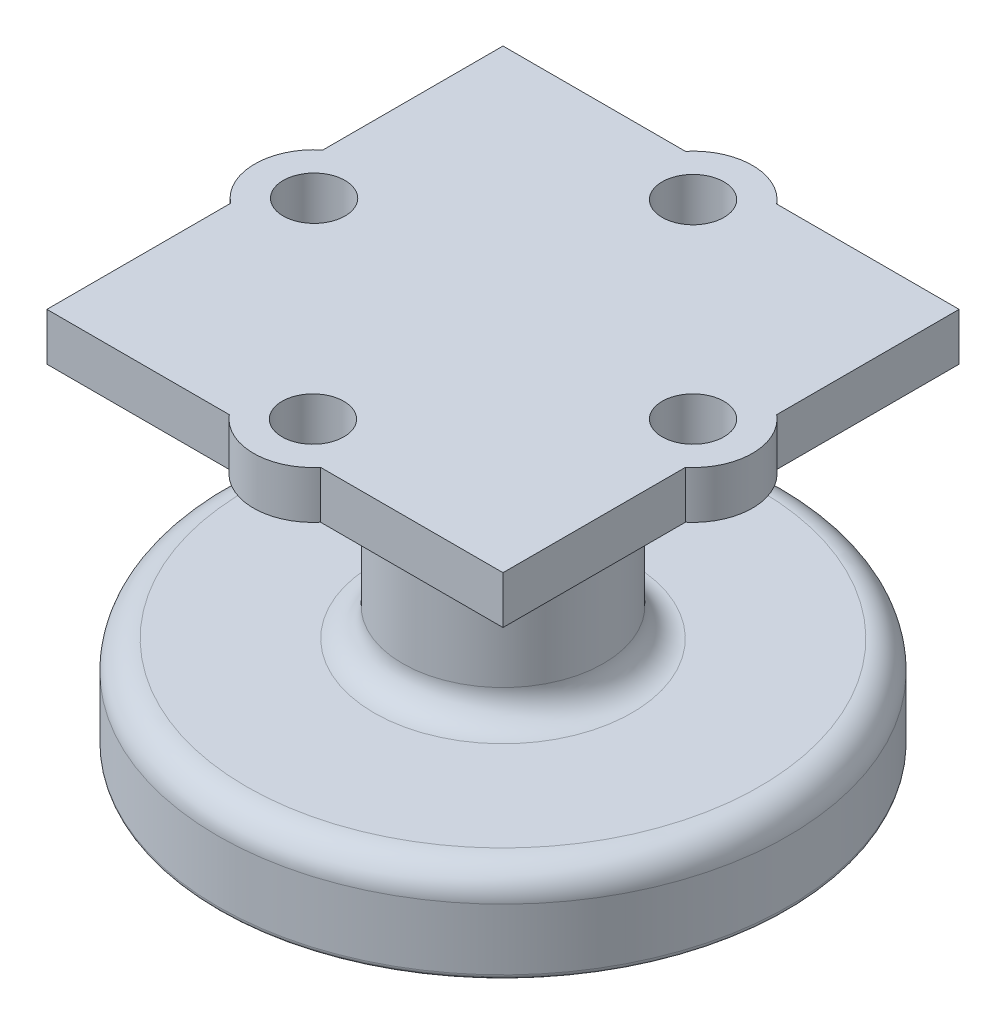
SolidWorks part; units mm, degrees
ref_plane "Спереди" through (0, 0, 0) normal (0, 0, 1) x (1, 0, 0)
ref_plane "Сверху" through (0, 0, 0) normal (0, 1, 0) x (1, 0, 0)
ref_plane "Справа" through (0, 0, 0) normal (1, 0, 0) x (0, 0, -1)
sketch "Sketch1" plane through (0, 0, 0) normal (0, 1, 0) x (1, 0, 0)
  line L0 (-24, -4.6689) -> (-24, -24)
  line L1 (-24, 24) -> (-4.8023, 24)
  line L2 (-24, 24) -> (-24, 5.0436)
  line L3 (-24, -24) -> (-4.8023, -24)
  line L4 (24, 24) -> (24, 4.8023)
  line L5 (-24, 24) -> (24, -24) construction
  line L6 (-24, -24) -> (24, 24) construction
  line L7 (-16, 16) -> (-4.8023, 16)
  line L8 (-16, 16) -> (-16, 4.9342)
  line L9 (-16, -16) -> (-4.8023, -16)
  line L10 (16, 16) -> (16, 4.8023)
  line L11 (-16, 16) -> (16, -16) construction
  line L12 (-16, -16) -> (16, 16) construction
  line L13 (-16, -4.5595) -> (-16, -16)
  line L14 (4.8023, 16) -> (16, 16)
  line L15 (4.8023, 24) -> (24, 24)
  line L16 (16, -4.8023) -> (16, -16)
  line L17 (4.8023, -16) -> (16, -16)
  line L18 (4.8023, -24) -> (24, -24)
  line L19 (24, -4.8023) -> (24, -24)
  circle A0 centre (-20.0657, 0.1873) radius 3.25
  circle A1 centre (0, 20) radius 3.25
  circle A2 centre (20, 0) radius 3.25
  circle A3 centre (0, -20) radius 3.25
  arc A4 (12, -16) -> (6.1732, -19.0234) centre (0, 0) ccw construction
  arc A5 (-24, 5.0436) -> (-24, -4.6689) centre (-20.0657, 0.1873) ccw
  arc A6 (-4.8023, 16) -> (4.8023, 16) centre (0, 20) ccw
  arc A7 (16, 4.8023) -> (16, -4.8023) centre (20, 0) ccw
  arc A8 (4.8023, -16) -> (-4.8023, -16) centre (0, -20) ccw
  arc A9 (-16, -4.5595) -> (-16, 4.9342) centre (-20.0657, 0.1873) ccw
  arc A10 (4.8023, 24) -> (-4.8023, 24) centre (0, 20) ccw
  arc A11 (24, -4.8023) -> (24, 4.8023) centre (20, 0) ccw
  arc A12 (-4.8023, -24) -> (4.8023, -24) centre (0, -20) ccw
  point P0 (0, 0)
  point P6 (0, 0)
  dimension "D3" = 40
  dimension "D4" = 6.5
  dimension "D5" = 12.5
  dimension "D6" = 6.5
  dimension "D7" = 12.5
  dimension "D8" = 6.5
  dimension "D9" = 12.5
  dimension "D10" = 6.5
  dimension "D11" = 12.5
  dimension "D1" = 48
  dimension "D2" = 32
  dimension "D12" = 32
extrude "Boss-Extrude1" add sketch "Sketch1" along normal blind 5 contours L4 A11 L19 L18 A12 L3 L0 A5 L2 L1 A10 L15 | A8 L9 L13 A9 L8 L7 A6 L14 L10 A7 L16 L17 | A1 | A3 | A2 | A0
ref_plane "Plane1" through (0, -65, 0) normal (0, -1, 0) x (-1, 0, 0)
sketch "Sketch2" plane through (0, 0, 0) normal (0, -1, 0) x (1, 0, 0)
  line L1 (-16.3247, -16.4535) -> (16.3247, -16.4535)
  line L2 (-16.3247, -16.4535) -> (-16.3247, 16.4535)
  line L3 (-16.3247, 16.4535) -> (16.3247, 16.4535)
  line L4 (16.3247, -16.4535) -> (16.3247, 16.4535)
  line L5 (-16.3247, -16.4535) -> (16.3247, 16.4535) construction
  line L6 (-16.3247, 16.4535) -> (16.3247, -16.4535) construction
  point P0 (0, 0)
extrude "Boss-Extrude2" add sketch "Sketch2" against normal up to surface (5 mm away) up to face at (20, 5, 3.25)
sketch "Sketch3" plane through (0, 0, 0) normal (0, -1, 0) x (-1, 0, 0)
  circle A0 centre (0, 0) radius 10.5672
extrude "Boss-Extrude3" add sketch "Sketch3" along normal blind 25
sketch "Sketch4" plane through (0, -25, 0) normal (0, -1, 0) x (-1, 0, 0)
  circle A0 centre (0, 0) radius 30
extrude "Boss-Extrude4" add sketch "Sketch4" along normal blind 10
fillet "Fillet1" radius 3 1 edges at (0, 0, 10.5672)
fillet "Fillet2" radius 0.56 1 edges at (0, -35, -30)
fillet "Fillet3" radius 3 2 edges at (0, -25, -10.5672) (0, -25, -30)
